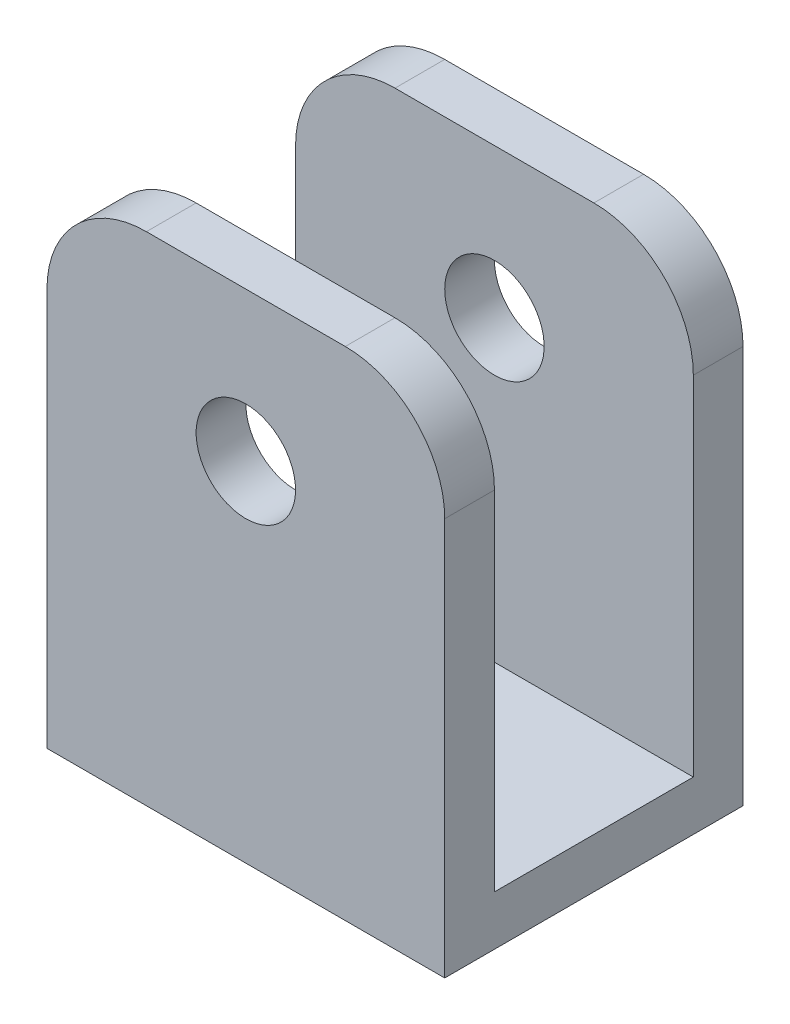
SolidWorks part; units mm, degrees
ref_plane "Front Plane" through (0, 0, 0) normal (0, 0, 1) x (1, 0, 0)
ref_plane "Top Plane" through (0, 0, 0) normal (0, 1, 0) x (1, 0, 0)
ref_plane "Right Plane" through (0, 0, 0) normal (1, 0, 0) x (0, 0, -1)
sketch "Sketch1" plane through (0, 0, 0) normal (0, 0, 1) x (1, 0, 0)
  line L0 (0, 80.8684) -> (0, -50.674) construction
  line L1 (-20, -35) -> (20, -35)
  line L2 (20, -35) -> (20, 5)
  line L3 (-20, -35) -> (-20, 5)
  line L4 (-10, 15) -> (10, 15)
  arc A0 (10, 15) -> (20, 5) centre (10, 5) cw
  circle A1 centre (0, 0) radius 5
  arc A2 (-20, 5) -> (-10, 15) centre (-10, 5) cw
  point P1 (0, -35)
  point P6 (0, 15)
  point P16 (-20, 15)
  dimension "D1" = 50
  dimension "D2" = 35
  dimension "D5" = 10
  dimension "D3" = 10
  dimension "D4" = 40
extrude "Boss-Extrude4" add sketch "Sketch1" along normal blind 5
sketch "Sketch4" plane through (0, 0, 0) normal (0, 0, -1) x (-1, 0, 0)
  line L1 (-20, -30) -> (20, -30)
  line L2 (-20, -30) -> (-20, -35)
  line L3 (-20, -35) -> (20, -35)
  line L4 (20, -30) -> (20, -35)
  line L5 (-20, -30) -> (20, -35) construction
  line L6 (-20, -35) -> (20, -30) construction
  point P0 (0, -32.5)
  dimension "D1" = 5
  dimension "D2" = 40
extrude "Boss-Extrude5" add sketch "Sketch4" along normal blind 20
sketch "Sketch5" plane through (0, 0, -20) normal (0, 0, -1) x (-1, 0, 0)
  line L0 (-20, 5) -> (-20, -35)
  line L1 (20, -35) -> (20, -30)
  line L2 (-20, -35) -> (20, -35)
  line L3 (-20, -30) -> (20, -30)
  line L4 (-10, 15) -> (10, 15)
  line L6 (20, 5) -> (20, -30)
  arc A0 (20, 5) -> (10, 15) centre (10, 5) ccw
  arc A1 (-20, 5) -> (-10, 15) centre (-10, 5) cw
  circle A2 centre (0, 0) radius 5
  dimension "D1" = 10
  dimension "D2" = 10
  dimension "D3" = 40
  dimension "D4" = 30
extrude "Boss-Extrude6" add sketch "Sketch5" along normal blind 5
sketch "Sketch7" plane through (0, -30, 0) normal (0, 1, 0) x (1, 0, 0)
  line L0 (-20, 0) -> (20, 0) construction
  line L1 (20, 20) -> (20, 0) construction
  line L2 (-10, 0) -> (-20, 0) construction
  line L4 (-20, 20) -> (-20, 0) construction
  circle A0 centre (-7, 10) radius 2
  circle A1 centre (7, 10) radius 2
  dimension "D1" = 4
  dimension "D2" = 4
  dimension "D3" = 10
  dimension "D4" = 13
  dimension "D5" = 10
  dimension "D6" = 13
extrude "Cut-Extrude1" cut sketch "Sketch7" against normal blind 15
